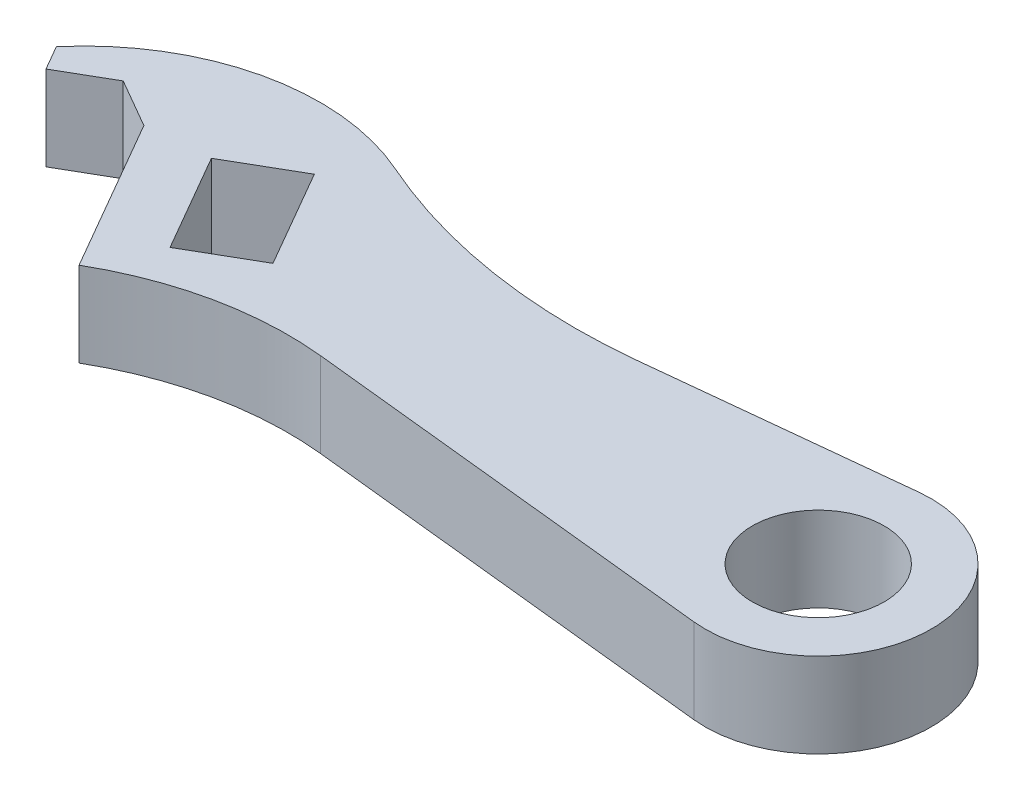
SolidWorks part; units mm, degrees
ref_plane "Front Plane" through (0, 0, 0) normal (0, 0, 1) x (1, 0, 0)
ref_plane "Top Plane" through (0, 0, 0) normal (0, 1, 0) x (1, 0, 0)
ref_plane "Right Plane" through (0, 0, 0) normal (1, 0, 0) x (0, 0, -1)
sketch "Sketch1" plane through (0, 0, 0) normal (0, 1, 0) x (1, 0, 0)
  line L0 (0, 0) -> (-99.0806, 0) construction
  line L1 (-1.2543, 11.9343) -> (-28.2897, 9.0927)
  line L2 (-45.5473, -7.2789) -> (-1.2543, -11.9343)
  line L3 (-88, 7.1064) -> (-86.5, 4.5083)
  line L4 (-86.5, 4.5083) -> (-81.3038, 7.5083)
  line L5 (-81.3038, 7.5083) -> (-76.1077, 4.5083)
  line L6 (-76.1077, 4.5083) -> (-66.7058, -11.7763)
  line L7 (-69.5096, 5.0801) -> (-63.5096, -5.3122)
  line L8 (-63.5096, -5.3122) -> (-56.5814, -1.3122)
  line L9 (-56.5814, -1.3122) -> (-62.5814, 9.0801)
  line L10 (-62.5814, 9.0801) -> (-69.5096, 5.0801)
  arc A0 (-1.2543, -11.9343) -> (-1.2543, 11.9343) centre (0, 0) ccw
  circle A1 centre (0, 0) radius 7
  arc A3 (-28.2897, 9.0927) -> (-58.7861, 13.8718) centre (-34.5614, 68.764) cw
  arc A4 (-58.7861, 13.8718) -> (-88, 7.1064) centre (-68.8798, -9) ccw
  arc A5 (-45.5473, -7.2789) -> (-66.7058, -11.7763) centre (-49.2058, -42.0872) ccw
  arc A6 (-12, 0) -> (-1.2543, -11.9343) centre (0, 0) ccw construction
  arc A7 (-1.2543, 11.9343) -> (-12, 0) centre (0, 0) ccw construction
  point P17 (-67.6619, 2.9801)
  point P22 (-63.2376, -8.187)
  point P23 (-61.4151, -7.8485)
  point P24 (-64.4634, 10.6434)
  point P25 (-59.8744, 7.1228)
  point P26 (0, 0)
  dimension "D2" = 14
  dimension "D4" = 60
  dimension "D5" = 25
  dimension "D6" = 35
  dimension "D1" = 5
  dimension "D3" = 12
  dimension "D8" = 16
  dimension "D13" = 8
  dimension "D14" = 12
  dimension "D15" = 4
  dimension "D16" = 60
  dimension "D7" = 100
  dimension "D9" = 3
  dimension "D10" = 6
  dimension "D11" = 6
  dimension "D12" = 30
  dimension "D17" = 8
  dimension "D18" = 15
extrude "Boss-Extrude1" add sketch "Sketch1" along normal mid plane 9
equation "\"A\"= 100"
equation "\"D7@Sketch1\"=\"A\""
